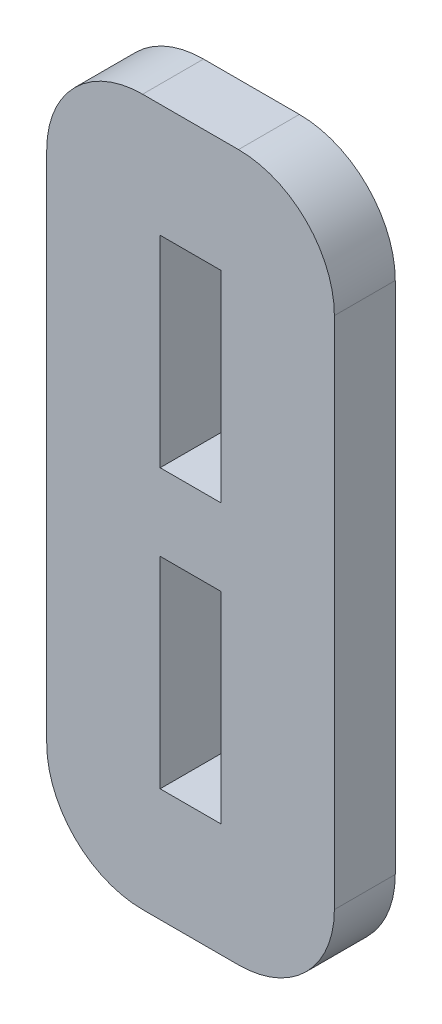
SolidWorks part; units mm, degrees
material "Mahogany"
ref_plane "Front Plane" through (0, 0, 0) normal (0, 0, 1) x (1, 0, 0)
ref_plane "Top Plane" through (0, 0, 0) normal (0, 1, 0) x (1, 0, 0)
ref_plane "Right Plane" through (0, 0, 0) normal (1, 0, 0) x (0, 0, -1)
sketch "Sketch1" plane through (0, 0, 0) normal (0, 0, 1) x (1, 0, 0)
  line L0 (35.75, 58.4125) -> (41.6625, 52.5) construction
  line L8 (41.6625, 27.5) -> (44.8375, 27.5) construction
  line L9 (41.6625, 38) -> (41.6625, 27.5) construction
  line L10 (44.8375, 27.5) -> (44.8375, 38) construction
  line L11 (44.8375, 38) -> (41.6625, 38) construction
  line L12 (41.6625, 42) -> (44.8375, 42) construction
  line L13 (41.6625, 52.5) -> (41.6625, 42) construction
  line L14 (44.8375, 42) -> (44.8375, 52.5) construction
  line L15 (44.8375, 52.5) -> (41.6625, 52.5) construction
  line L16 (41.6625, 27.5) -> (44.8375, 27.5)
  line L17 (41.6625, 38) -> (41.6625, 27.5)
  line L18 (44.8375, 27.5) -> (44.8375, 38)
  line L19 (44.8375, 38) -> (41.6625, 38)
  line L20 (41.6625, 42) -> (44.8375, 42)
  line L21 (41.6625, 52.5) -> (41.6625, 42)
  line L22 (44.8375, 42) -> (44.8375, 52.5)
  line L23 (44.8375, 52.5) -> (41.6625, 52.5)
  line L24 (35.75, 52.5) -> (35.75, 27.5) construction
  line L25 (50.75, 27.5) -> (50.75, 52.5) construction
  line L26 (-1.5875, 17.5) -> (88.0875, 17.5) construction
  line L27 (-1.5875, 62.5) -> (88.0875, 62.5) construction
  line L28 (35.75, 62.5) -> (35.75, 17.5) construction
  line L29 (50.75, 17.5) -> (50.75, 62.5) construction
  line L30 (35.75, 17.5) -> (50.75, 17.5) construction
  line L31 (35.75, 62.5) -> (50.75, 62.5) construction
  line L33 (35.75, 21.5875) -> (50.75, 21.5875)
  line L34 (35.75, 21.5875) -> (35.75, 58.4125)
  line L35 (35.75, 58.4125) -> (50.75, 58.4125)
  line L36 (50.75, 21.5875) -> (50.75, 58.4125)
  line L37 (35.75, 21.5875) -> (50.75, 58.4125) construction
  line L38 (35.75, 58.4125) -> (50.75, 21.5875) construction
  point P15 (43.25, 40)
  point P31 (50.75, 40)
  point P33 (43.25, 62.5)
  dimension "D1" = 45
extrude "Boss-Extrude1" add sketch "Sketch1" along normal blind 3.175
fillet "Fillet1" radius 5 4 edges at (35.75, 58.4125, 1.5875) (50.75, 58.4125, 1.5875) (35.75, 21.5875, 1.5875) (50.75, 21.5875, 1.5875)
equation "\"prop-dist-width\"= 86.5mm"
equation "\"prop-dist-length\"= 80mm"
equation "\"prop-hole-diameter\"= 11mm"
equation "\"prop-boost\"= 4.4mm"
equation "\"back-drop\"= 5mm"
equation "\"T\"= 0.125in'Material Thickness"
equation "\"tof_c2c\"= 19.9mm'Center to center distance of TOF sensor holes"
equation "\"tof_d\"= 3mm'TOF hole diameter"
equation "\"tof_w\"= 12.6mm'TOF width"
equation "\"tof_l\"= 15.6mm'TOF length"
equation "\"pin_w\"= 2.3mm'A standard IO Pin socket width"
equation "\"pin_l\"= 2.5mm'A standard IO Pin socket length"
equation "\"esp_pin_num\"= 8'Number of pins on one side of the ESP"
equation "\"esp_l\"= 40mm'ESP length"
equation "\"esp_w\"= 27mm'ESP width"
equation "\"esp_pin_inset\"= 3mm'Distance that ESP pins are inset"
equation "\"bat_l\"= 27mm'Battery length"
equation "\"bat_w\"= 20mm'Battery width"
equation "\"bat_h\"= 6mm'Battery thickness"
equation "\"boost_w\"= 17.2mm"
equation "\"boost_l\"= 37mm"
equation "\"boost_hole_inset\"= 2.2mm"
equation "\"boost_hole_dist\"= 7mm"
equation "\"boost_hole_d\"= 2mm"
equation "\"prop-dist\"= 80mm"
equation "\"prop-hole-depth\"= 9mm"
equation "\"rivet-extension\"= 12mm"
equation "\"rivet-hole-extension\"= 7mm"
equation "\"rivet-hole-diameter\"= 3.8mm"
equation "\"ski-length\"= 100mm"
equation "\"th\"= 0.125in'material thickness"
equation "\"ski-height\"= 30mm"
equation "\"ski-curve-gap\"= 60mm"
equation "\"ski-curve-height\"= \"rivet-hole-extension\""
equation "\"min-width\"= 4mm"
equation "\"prop-hole-diameter-small\"= 8.6mm"
equation "\"support_width\"= 10mm"
equation "\"support_gap\"= 25mm"
equation "\"support_height\"= 21.5mm"
equation "\"D1@Boss-Extrude1\"=\"T\""
